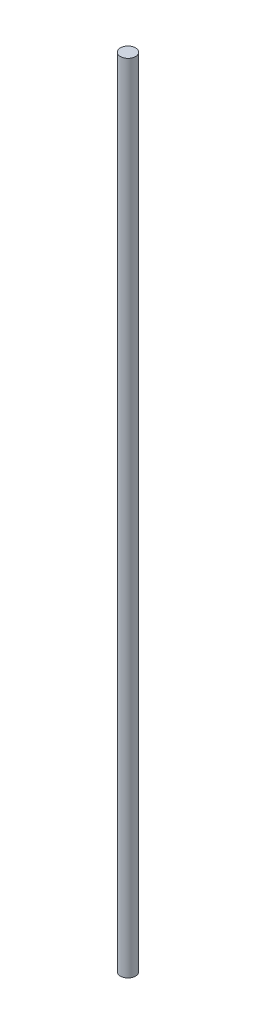
SolidWorks part; units mm, degrees
ref_plane "Front Plane" through (0, 0, 0) normal (0, 0, 1) x (1, 0, 0)
ref_plane "Top Plane" through (0, 0, 0) normal (0, 1, 0) x (1, 0, 0)
ref_plane "Right Plane" through (0, 0, 0) normal (1, 0, 0) x (0, 0, -1)
sketch "Sketch1" plane through (0, 0, 0) normal (0, 1, 0) x (1, 0, 0)
  circle A0 centre (0, 0) radius 4
  dimension "D1" = 8
extrude "Boss-Extrude1" add sketch "Sketch1" along normal up to surface (420 mm away)
